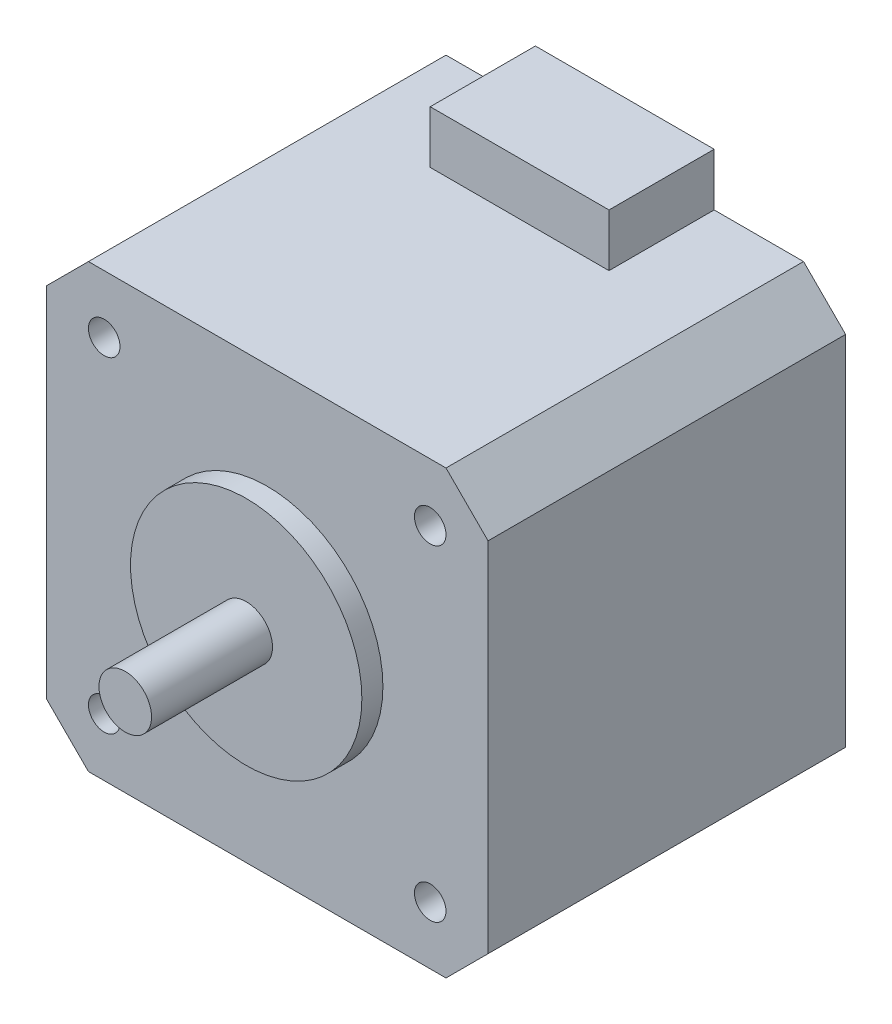
SolidWorks part; units mm, degrees
ref_plane "Plan de face" through (0, 0, 0) normal (0, 0, 1) x (1, 0, 0)
ref_plane "Plan de dessus" through (0, 0, 0) normal (0, 1, 0) x (1, 0, 0)
ref_plane "Plan de droite" through (0, 0, 0) normal (1, 0, 0) x (0, 0, -1)
sketch "Esquisse1" plane through (0, 0, 0) normal (0, 0, 1) x (1, 0, 0)
  line L1 (0, 0) -> (42, 0)
  line L2 (0, 0) -> (0, 42)
  line L3 (0, 42) -> (42, 42)
  line L4 (42, 0) -> (42, 42)
  dimension "D1" = 42
  dimension "D2" = 42
extrude "Boss.-Extru.1" add sketch "Esquisse1" along normal blind 34
sketch "Esquisse2" plane through (0, 0, 34) normal (0, 0, 1) x (1, 0, 0)
  line L0 (0, 42) -> (0, 0) construction
  line L1 (0, 0) -> (42, 0) construction
  circle A0 centre (21, 21) radius 11
  point P4 (0, 21)
  point P7 (21, 0)
  dimension "D1" = 22
  dimension "D2" = 0
  dimension "D3" = 0
extrude "Boss.-Extru.2" add sketch "Esquisse2" along normal blind 2
sketch "Esquisse3" plane through (0, 0, 36) normal (0, 0, 1) x (1, 0, 0)
  circle A0 centre (21, 21) radius 2.5
  dimension "D1" = 5
extrude "Boss.-Extru.3" add sketch "Esquisse3" along normal blind 11.5
chamfer "Chanfrein1" distance 4 angle 45 4 edges at (42, 42, 17) (42, 0, 17) (0, 0, 17) (0, 42, 17)
sketch "Esquisse4" plane through (0, 42, 0) normal (0, 1, 0) x (1, 0, 0)
  line L0 (38, 0) -> (4, 0) construction
  line L1 (12.5, 0) -> (29.5, 0)
  line L2 (12.5, 0) -> (12.5, -10)
  line L3 (12.5, -10) -> (29.5, -10)
  line L4 (29.5, 0) -> (29.5, -10)
  point P6 (21, 0)
  point P7 (21, 0)
  dimension "D1" = 17
  dimension "D2" = 10
  dimension "D3" = 0
extrude "Boss.-Extru.4" add sketch "Esquisse4" along normal blind 5
sketch "Esquisse5" plane through (0, 0, 34) normal (0, 0, 1) x (1, 0, 0)
  line L0 (0, 38) -> (0, 4) construction
  line L3 (38, 42) -> (4, 42) construction
  circle A0 centre (5.5, 36.5) radius 1.5
  circle A1 centre (36.5, 36.5) radius 1.5
  circle A2 centre (36.5, 5.5) radius 1.5
  circle A3 centre (5.5, 5.5) radius 1.5
  point P8 (0, 0)
  point P9 (0, 0)
  point P10 (0, 0)
  point P11 (0, 0)
  point P12 (6.0987, 37.8458)
  dimension "D4" = 5.5
  dimension "D5" = 3
  dimension "D1" = 31
  dimension "D2" = 31
  dimension "D3" = 5.5
extrude "Enlèv. mat.-Extru.1" cut sketch "Esquisse5" against normal blind 5
